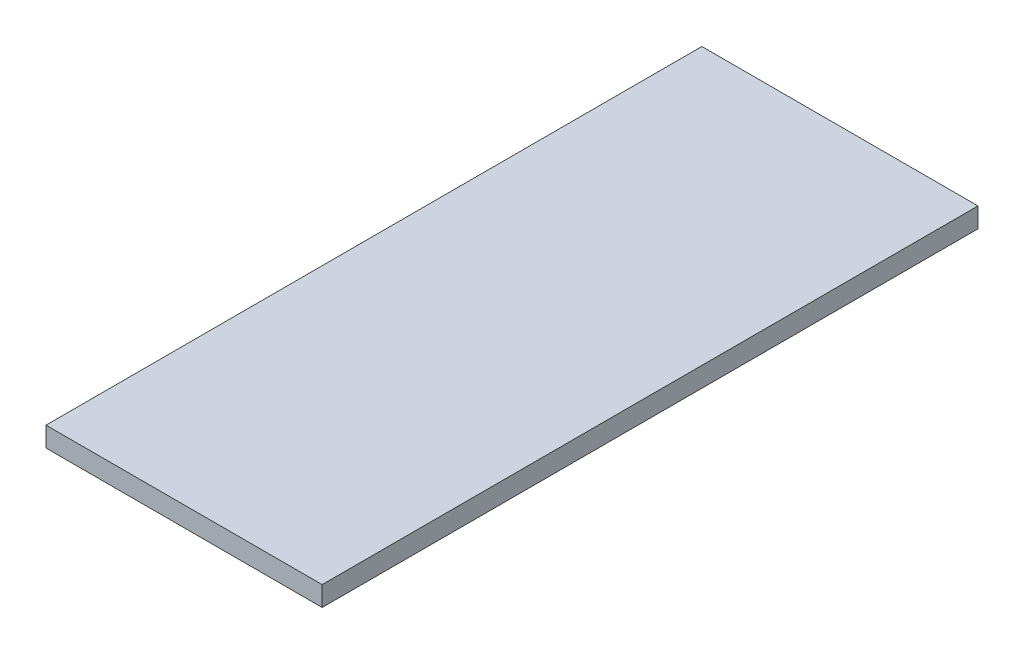
SolidWorks part; units mm, degrees
material "Pine"
ref_plane "Front Plane" through (0, 0, 0) normal (0, 0, 1) x (1, 0, 0)
ref_plane "Top Plane" through (0, 0, 0) normal (0, 1, 0) x (1, 0, 0)
ref_plane "Right Plane" through (0, 0, 0) normal (1, 0, 0) x (0, 0, -1)
sketch "s" plane through (0, 0, 0) normal (0, 1, 0) x (1, 0, 0)
  line L1 (-127, 0) -> (127, 0)
  line L2 (-127, 0) -> (-127, 603.25)
  line L3 (-127, 603.25) -> (127, 603.25)
  line L4 (127, 0) -> (127, 603.25)
  point P4 (0, 0)
  dimension "D1" = 254
  dimension "D2" = 603.25
extrude "Boss-Extrude1" add sketch "s" along normal blind 18.2562
